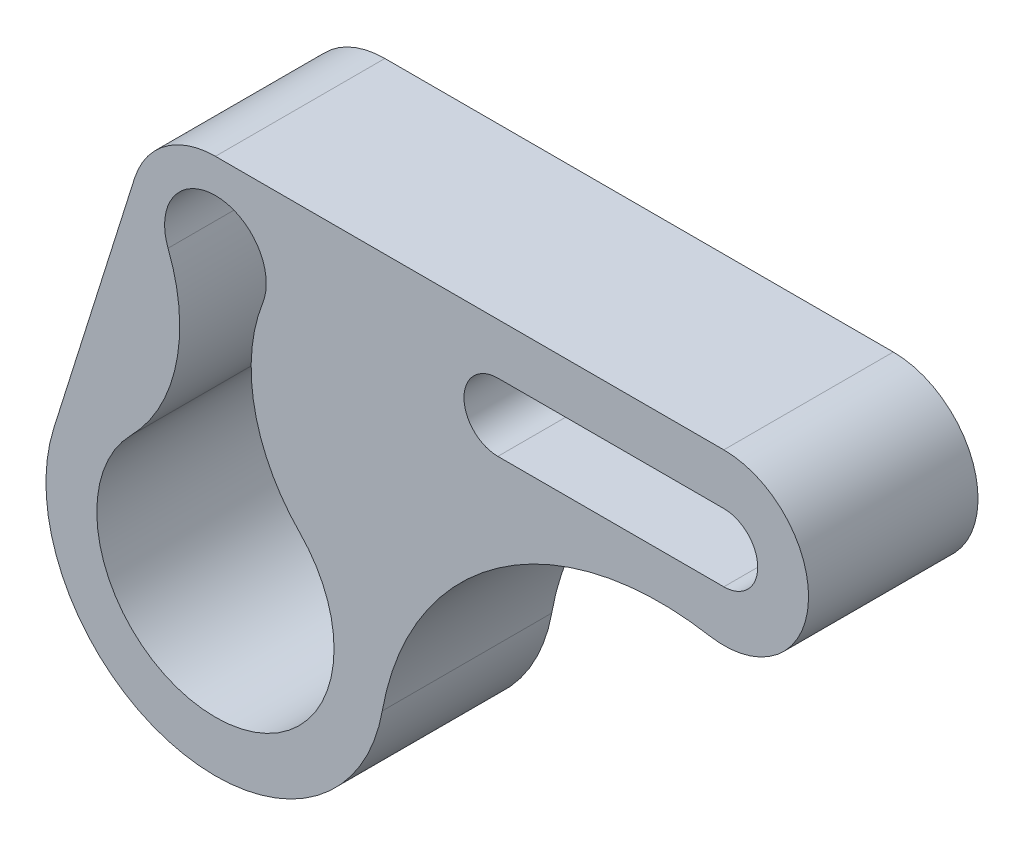
SolidWorks part; units mm, degrees
ref_plane "Front Plane" through (0, 0, 0) normal (0, 0, 1) x (1, 0, 0)
ref_plane "Top Plane" through (0, 0, 0) normal (0, 1, 0) x (1, 0, 0)
ref_plane "Right Plane" through (0, 0, 0) normal (1, 0, 0) x (0, 0, -1)
sketch "Sketch1" plane through (0, 0, 0) normal (0, 0, 1) x (1, 0, 0)
  line L0 (0, 0) -> (0, -33183.5555) construction
  line L1 (0, 0) -> (-33183.5555, 0) construction
  line L2 (50, 50) -> (90, 50) construction
  line L3 (50, 56) -> (90, 56)
  line L4 (50, 44) -> (90, 44)
  line L5 (90, 65) -> (0, 65)
  line L7 (-14.3091, 54.5) -> (-28.6182, 9)
  arc A0 (-14.9565, 14.7412) -> (14.9565, 14.7412) centre (0, 0) ccw
  arc A1 (8.3822, 46.7231) -> (-8.3822, 46.7231) centre (0, 50) ccw
  arc A2 (-8.3822, 46.7231) -> (-14.9565, 14.7412) centre (-36.323, 35.8) cw
  arc A3 (8.3822, 46.7231) -> (14.9565, 14.7412) centre (36.323, 35.8) ccw
  arc A4 (50, 56) -> (50, 44) centre (50, 50) ccw
  arc A5 (90, 44) -> (90, 56) centre (90, 50) ccw
  arc A6 (87.4066, 35.2259) -> (90, 65) centre (90, 50) ccw
  arc A7 (-28.6182, 9) -> (29.5356, -5.2579) centre (0, 0) ccw
  arc A8 (29.5356, -5.2579) -> (87.4066, 35.2259) centre (78.7617, -14.0211) cw
  arc A11 (0, 65) -> (-14.3091, 54.5) centre (0, 50) ccw
  point P15 (70, 50)
  dimension "D1" = 42
  dimension "D2" = 18
  dimension "D4" = 30
  dimension "D5" = 30
  dimension "D8" = 6
  dimension "D9" = 30
  dimension "D10" = 60
  dimension "D11" = 50
  dimension "D12" = 15
  dimension "D3" = 50
  dimension "D6" = 40
  dimension "D7" = 50
extrude "Boss-Extrude1" add sketch "Sketch1" along normal mid plane 30
